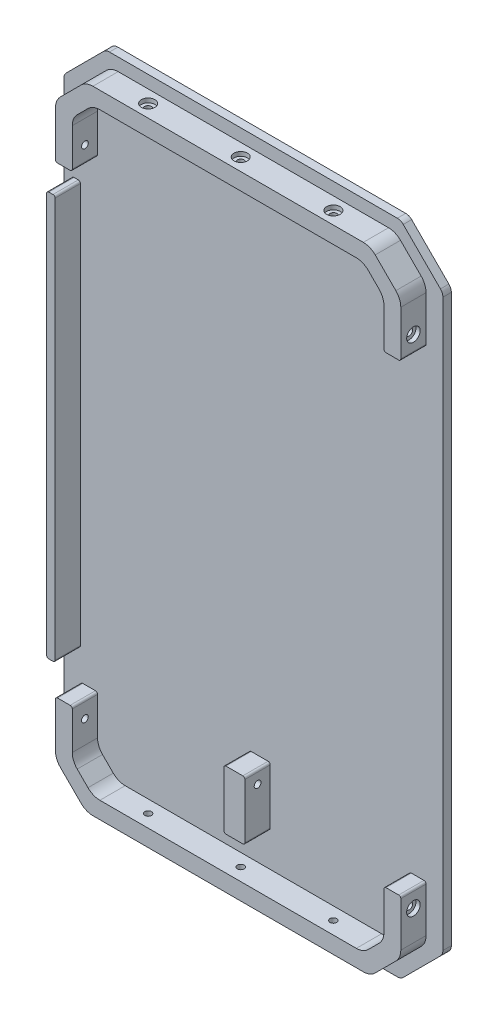
SolidWorks part; units mm, degrees
material "6061-T4 (SS)"
ref_plane "前视基准面" through (0, 0, 0) normal (0, 0, 1) x (1, 0, 0)
ref_plane "上视基准面" through (0, 0, 0) normal (0, 1, 0) x (1, 0, 0)
ref_plane "右视基准面" through (0, 0, 0) normal (1, 0, 0) x (0, 0, -1)
sketch "草图1" plane through (0, 0, 0) normal (0, 0, 1) x (1, 0, 0)
  line L1 (0, 0) -> (-90, 0)
  line L2 (0, 0) -> (0, 156)
  line L3 (0, 156) -> (-90, 156)
  line L4 (-90, 0) -> (-90, 156)
  dimension "D1" = 90
  dimension "D2" = 156
extrude "凸台-拉伸1" add sketch "草图1" along normal blind 2
chamfer "倒角1" distance 10 angle 45 4 edges at (0, 0, 1) (-90, 0, 1) (-90, 156, 1) (0, 156, 1)
fillet "外角" radius 2 8 edges at (-90, 10, 1) (-80, 0, 1) (-10, 0, 1) (0, 10, 1) (0, 146, 1) (-10, 156, 1) (-90, 146, 1) (-80, 156, 1)
sketch "草图2" plane through (0, 0, 2) normal (0, 0, 1) x (1, 0, 0)
  line L0 (-10.8284, 156) -> (-79.1716, 156) construction
  line L1 (-78.7574, 153) -> (-11.2426, 153)
  line L2 (-87, 144.7574) -> (-87, 11.2426)
  line L3 (-78.7574, 3) -> (-11.2426, 3)
  line L4 (-3, 144.7574) -> (-3, 11.2426)
  line L5 (-79.1716, 0) -> (-10.8284, 0) construction
  line L6 (-90, 145.1716) -> (-90, 10.8284) construction
  line L7 (0, 10.8284) -> (0, 145.1716) construction
  line L8 (-87, 144.7574) -> (-78.7574, 153)
  line L10 (-11.2426, 153) -> (-3, 144.7574)
  line L11 (-85, 151) -> (-82.8787, 148.8787) construction
  line L12 (-87, 11.2426) -> (-78.7574, 3)
  line L14 (-3, 11.2426) -> (-11.2426, 3)
  line L19 (-80.5858, 155.4142) -> (-89.4142, 146.5858) construction
  line L20 (-5, 151) -> (-7.1213, 148.8787) construction
  line L21 (-0.5858, 146.5858) -> (-9.4142, 155.4142) construction
  line L22 (-5, 5) -> (-7.1213, 7.1213) construction
  line L23 (-9.4142, 0.5858) -> (-0.5858, 9.4142) construction
  line L24 (-85, 5) -> (-82.8787, 7.1213) construction
  line L25 (-89.4142, 9.4142) -> (-80.5858, 0.5858) construction
  dimension "D1" = 3
  dimension "D2" = 3
  dimension "D3" = 3
  dimension "D4" = 3
  dimension "D5" = 90
  dimension "D6" = 90
  dimension "D7" = 90
  dimension "D8" = 90
extrude "凸台-拉伸2" add sketch "草图2" along normal blind 6
sketch "草图4" plane through (-87, 0, 0) normal (-1, 0, 0) x (0, 0, 1)
  line L1 (5, 11.2426) -> (5, 144.7574) construction
  line L2 (8, 11.2426) -> (2, 11.2426) construction
  line L3 (0, 156) -> (2, 156) construction
  line L4 (2, 0) -> (0, 0) construction
  line L5 (8, 144.7574) -> (2, 144.7574) construction
  circle A0 centre (5, 137) radius 0.8
  circle A1 centre (5, 19) radius 0.8
  dimension "D3" = 19
  dimension "D2" = 19
shell "抽壳3" thickness 4
sketch "草图11" plane through (0, 0, 8) normal (0, 0, 1) x (1, 0, 0)
  line L1 (-96.1833, 132) -> (4.7245, 132)
  line L2 (-96.1833, 132) -> (-96.1833, 24)
  line L3 (-96.1833, 24) -> (4.7245, 24)
  line L4 (4.7245, 132) -> (4.7245, 24)
  line L6 (-10.8284, 156) -> (-79.1716, 156) construction
  line L7 (-79.1716, 0) -> (-10.8284, 0) construction
  dimension "D1" = 24
  dimension "D2" = 24
extrude "切除-拉伸8" [suppressed] cut sketch "草图11" against normal blind 6
sketch "草图17" plane through (0, 0, 8) normal (0, 0, 1) x (1, 0, 0)
  line L0 (-87, 144.7574) -> (-87, 11.2426) construction
  line L1 (-104.3996, 159.6799) -> (-86, 159.6799)
  line L2 (-104.3996, 159.6799) -> (-104.3996, -3.9693)
  line L3 (-104.3996, -3.9693) -> (-86, -3.9693)
  line L4 (-86, 159.6799) -> (-86, -3.9693)
  line L5 (-3, 11.2426) -> (-3, 144.7574) construction
  line L6 (12.4597, 159.6799) -> (-4, 159.6799)
  line L7 (12.4597, 159.6799) -> (12.4597, -8.3787)
  line L8 (12.4597, -8.3787) -> (-4, -8.3787)
  line L9 (-4, 159.6799) -> (-4, -8.3787)
  dimension "D1" = 1
  dimension "D2" = 1
extrude "切除-拉伸14" cut sketch "草图17" against normal blind 6
sketch "草图8" plane through (0, 0, 8) normal (0, 0, 1) x (1, 0, 0)
  line L5 (-10.8284, 156) -> (-79.1716, 156) construction
  line L6 (-100.9873, 133) -> (8.5404, 133)
  line L12 (-100.9873, 133) -> (-100.9873, 23)
  line L13 (-100.9873, 23) -> (8.5404, 23)
  line L14 (8.5404, 133) -> (8.5404, 23)
  line L15 (-79.1716, 0) -> (-10.8284, 0) construction
  dimension "D1" = 23
  dimension "D2" = 23
extrude "刀路" cut sketch "草图8" against normal blind 6
sketch "草图21" plane through (0, 0, 2) normal (0, 0, 1) x (1, 0, 0)
  line L0 (-82, 142.1005) -> (-82, 144.1005)
  line L2 (-83, 143.1005) -> (-83, 133)
  line L3 (-83, 133) -> (-82, 133)
  line L4 (-82, 142.1005) -> (-82, 133)
  line L5 (-83, 143.1005) -> (-77.1005, 149) construction
  line L6 (-82, 144.1005) -> (-83, 143.1005)
  line L7 (-8, 142.1005) -> (-8, 144.1005)
  line L9 (-7, 143.1005) -> (-7, 133)
  line L10 (-7, 133) -> (-8, 133)
  line L11 (-8, 142.1005) -> (-8, 133)
  line L12 (-12.8995, 149) -> (-7, 143.1005) construction
  line L13 (-7, 143.1005) -> (-8, 144.1005)
  line L14 (-82, 13.8995) -> (-82, 11.8995)
  line L16 (-83, 12.8995) -> (-83, 23)
  line L17 (-83, 23) -> (-82, 23)
  line L18 (-82, 13.8995) -> (-82, 23)
  line L19 (-77.1005, 7) -> (-83, 12.8995) construction
  line L20 (-82, 11.8995) -> (-83, 12.8995)
  line L21 (-8, 13.8995) -> (-8, 11.8995)
  line L23 (-7, 12.8995) -> (-7, 23)
  line L24 (-7, 23) -> (-8, 23)
  line L25 (-8, 13.8995) -> (-8, 23)
  line L26 (-7, 12.8995) -> (-12.8995, 7) construction
  line L27 (-8, 11.8995) -> (-7, 12.8995)
  line L28 (-4, 133) -> (-7, 133) construction
  line L29 (-7, 23) -> (-4, 23) construction
extrude "凸台-拉伸5" add sketch "草图21" along normal blind 6
sketch "草图5" plane through (0, 3, 0) normal (0, -1, 0) x (-1, 0, 0)
  line L0 (45, -5) -> (45, -8) construction
  line L1 (78.7574, -8) -> (11.2426, -8) construction
  circle A1 centre (67, -5) radius 0.8
  circle A2 centre (23, -5) radius 0.8
  circle A3 centre (45, -5) radius 0.8
  dimension "D1" = 22
  dimension "D2" = 22
extrude "上下螺孔" cut sketch "草图5" against normal blind 200
fillet "拼接外角" radius 4 8 edges at (-78.7574, 3, 5) (-11.2426, 3, 5) (-11.2426, 153, 5) (-78.7574, 153, 5) (-4, 10.2426, 5) (-86, 10.2426, 5) (-86, 145.7574, 5) (-4, 145.7574, 5)
extrude "盖子螺孔" cut sketch "草图4" against normal blind 100
sketch "草图6" plane through (0, 0, 2) normal (0, 0, 1) x (1, 0, 0)
  line L0 (-79.1716, 0) -> (-10.8284, 0) construction
  line L5 (-90, 145.1716) -> (-90, 10.8284) construction
  line L10 (-90, 145.1716) -> (-90, 10.8284) construction
  line L17 (-51, 141) -> (-46, 141)
  line L18 (-51, 141) -> (-51, 127)
  line L19 (-46, 15) -> (-41, 15)
  line L20 (-46, 141) -> (-46, 127)
  line L25 (-46, 29) -> (-46, 15)
  line L26 (-51, 127) -> (-46, 127)
  line L28 (-46, 29) -> (-41, 29)
  line L30 (-41, 29) -> (-41, 15)
  line L31 (-10.8284, 156) -> (-79.1716, 156) construction
  dimension "D1" = 39
  dimension "D2" = 5
  dimension "D3" = 15
  dimension "D4" = 15
  dimension "D5" = 14
  dimension "D6" = 14
  dimension "D7" = 44
  dimension "D8" = 5
extrude "C板固定" add sketch "草图6" along normal blind 6
sketch "草图9" plane through (-41, 0, 0) normal (1, 0, 0) x (0, 0, -1)
  line L1 (-8, 29) -> (-2, 29) construction
  line L2 (-8, 127) -> (-2, 127) construction
  circle A1 centre (-5, 26) radius 0.8
  circle A2 centre (-5, 130) radius 0.8
  dimension "D1" = 3
  dimension "D2" = 3
extrude "C板螺纹" cut sketch "草图9" against normal blind 50
sketch "草图23" plane through (-86, 0, 0) normal (-1, 0, 0) x (0, 0, 1)
  circle A0 centre (5, 137) radius 1.6
  circle A1 centre (5, 19) radius 1.6
extrude "切除-拉伸16" cut sketch "草图23" against normal blind 1
sketch "草图24" plane through (-4, 0, 0) normal (1, 0, 0) x (0, 0, -1)
  circle A0 centre (-5, 19) radius 1.6
  circle A1 centre (-5, 137) radius 1.6
extrude "切除-拉伸17" cut sketch "草图24" against normal blind 1
sketch "草图22" plane through (0, 3, 0) normal (0, -1, 0) x (-1, 0, 0)
  circle A0 centre (67, -5) radius 1.6
  circle A1 centre (45, -5) radius 1.6
  circle A2 centre (23, -5) radius 1.6
extrude "切除-拉伸15" cut sketch "草图22" against normal blind 1
sketch "草图13" plane through (0, 153, 0) normal (0, 1, 0) x (1, 0, 0)
  circle A0 centre (-67, -5) radius 1.6
  circle A1 centre (-45, -5) radius 1.6
  circle A2 centre (-23, -5) radius 1.6
extrude "切除-拉伸10" cut sketch "草图13" against normal blind 1
sketch "草图18" plane through (0, 0, 2) normal (0, 0, 1) x (1, 0, 0)
  line L0 (-10.8284, 156) -> (-79.1716, 156) construction
  line L1 (-88.0781, 126) -> (-86.0781, 126)
  line L2 (-88.0781, 126) -> (-88.0781, 30)
  line L3 (-88.0781, 30) -> (-86.0781, 30)
  line L4 (-86.0781, 126) -> (-86.0781, 30)
  line L5 (-79.1716, 0) -> (-10.8284, 0) construction
  dimension "D1" = 2
  dimension "D2" = 30
  dimension "D3" = 30
extrude "凸台-拉伸4" add sketch "草图18" along normal blind 6
fillet "圆角1" radius 4 8 edges at (-77.1005, 7, 5) (-12.8995, 7, 5) (-12.8995, 149, 5) (-77.1005, 149, 5) (-8, 144.1005, 5) (-82, 144.1005, 5) (-8, 11.8995, 5) (-82, 11.8995, 5)
fillet "圆角2" radius 0.5 20 edges at (-41, 15, 5) (-46, 15, 5) (-46, 29, 5) (-41, 29, 5) (-86, 133, 5) (-82, 133, 5) (-86, 23, 5) (-82, 23, 5) (-4, 23, 5) (-8, 23, 5) (-8, 133, 5) (-4, 133, 5) (-88.0781, 30, 5) (-86.0781, 30, 5) (-88.0781, 126, 5) (-86.0781, 126, 5) (-51, 141, 5) (-51, 127, 5) (-46, 127, 5) (-46, 141, 5)
sketch "草图25" plane through (0, 0, 2) normal (0, 0, 1) x (1, 0, 0)
  line L1 (-60.3954, 146.1963) -> (-35.8637, 146.1963)
  line L2 (-60.3954, 146.1963) -> (-60.3954, 118.3183)
  line L3 (-60.3954, 118.3183) -> (-35.8637, 118.3183)
  line L4 (-35.8637, 146.1963) -> (-35.8637, 118.3183)
extrude "切除-拉伸18" cut sketch "草图25" along normal blind 10
